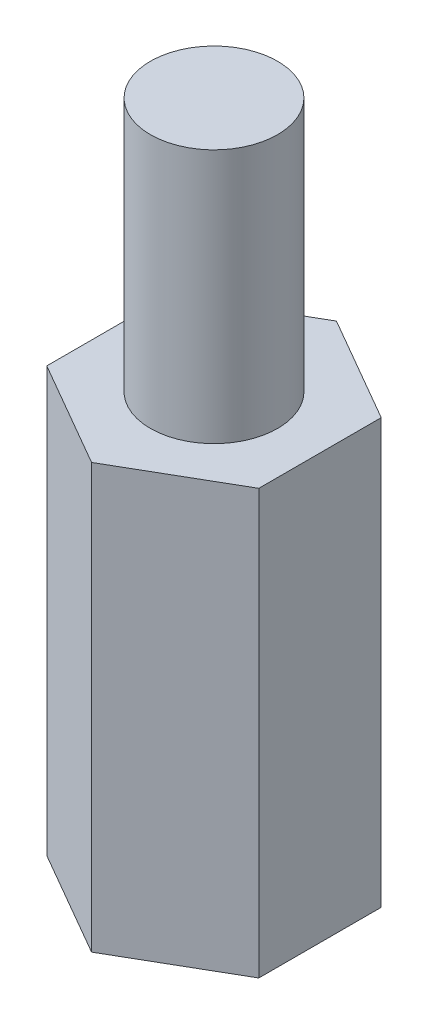
SolidWorks part; units mm, degrees
material "Brass"
ref_plane "Front Plane" through (0, 0, 0) normal (0, 0, 1) x (1, 0, 0)
ref_plane "Top Plane" through (0, 0, 0) normal (0, 1, 0) x (1, 0, 0)
ref_plane "Right Plane" through (0, 0, 0) normal (1, 0, 0) x (0, 0, -1)
sketch "Sketch1" plane through (0, 0, 0) normal (0, 1, 0) x (1, 0, 0)
  line L0 (0, 2.8868) -> (0, 0) construction
  line L1 (2.5, -1.4434) -> (2.5, 1.4434)
  line L2 (2.5, 1.4434) -> (0, 2.8868)
  line L3 (0, 2.8868) -> (-2.5, 1.4434)
  line L4 (-2.5, 1.4434) -> (-2.5, -1.4434)
  line L5 (-2.5, -1.4434) -> (0, -2.8868)
  line L6 (0, -2.8868) -> (2.5, -1.4434)
  circle A0 centre (0, 0) radius 2.5 construction
  dimension "D1" = 5
extrude "Boss-Extrude1" add sketch "Sketch1" along normal blind 10
sketch "Sketch2" plane through (0, 10, 0) normal (0, 1, 0) x (1, 0, 0)
  circle A0 centre (0, 0) radius 1.5
  dimension "D1" = 3
extrude "Boss-Extrude2" add sketch "Sketch2" along normal blind 6
sketch "Sketch3" plane through (0, 0, 0) normal (0, -1, 0) x (1, 0, 0)
  circle A0 centre (0, 0) radius 1.35
  dimension "D1" = 2.7
extrude "Cut-Extrude1" cut sketch "Sketch3" against normal blind 6
